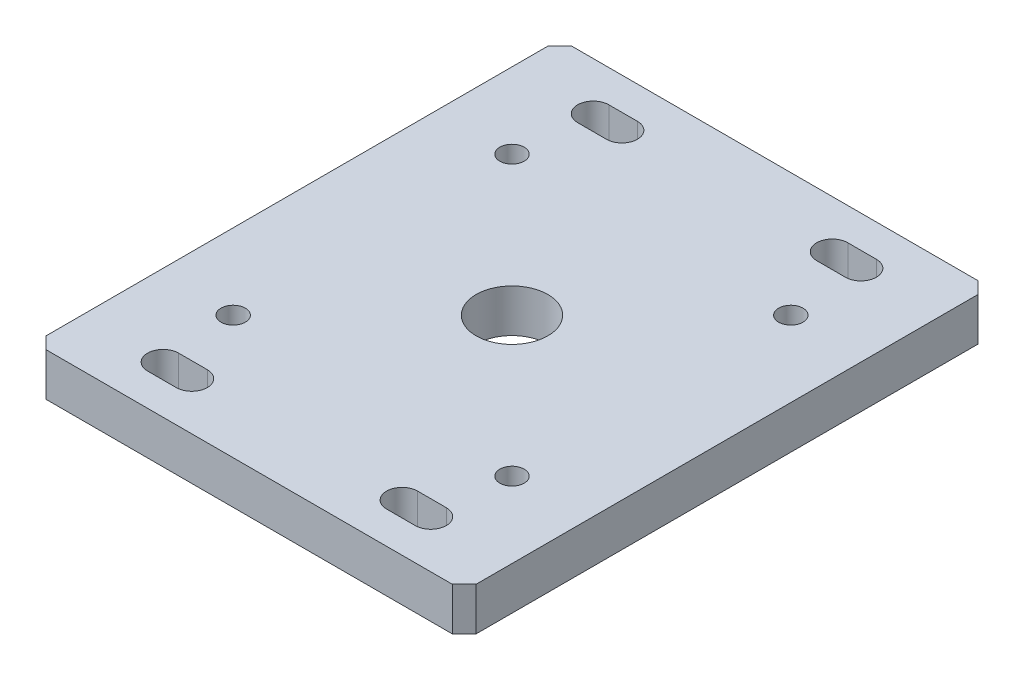
SolidWorks part; units mm, degrees
ref_plane "前基準面" through (0, 0, 0) normal (0, 0, 1) x (1, 0, 0)
ref_plane "上基準面" through (0, 0, 0) normal (0, 1, 0) x (1, 0, 0)
ref_plane "右基準面" through (0, 0, 0) normal (1, 0, 0) x (0, 0, -1)
sketch "草圖1" plane through (0, 0, 0) normal (1, 0, 0) x (0, 0, -1)
  line L1 (-110, 18) -> (110, 18)
  line L2 (-110, 18) -> (-110, 0)
  line L4 (110, 18) -> (110, 0)
  line L5 (-110, 0) -> (110, 0)
  line L7 (0, 36.9841) -> (0, -23.6317) construction
  dimension "D2" = 220
  dimension "D6" = 18
extrude "伸長1" add sketch "草圖1" along normal mid plane 180
sketch "草圖2" plane through (0, 0, 0) normal (0, -1, 0) x (1, 0, 0)
  circle A0 centre (0, 0) radius 15
  dimension "D1" = 30
extrude "除料-伸長1" cut sketch "草圖2" against normal up to next
chamfer "導角1" distance 5 angle 45 4 edges at (-90, 9, -110) (-90, 9, 110) (90, 9, 110) (90, 9, -110)
sketch "草圖4" plane through (0, 0, 0) normal (0, -1, 0) x (1, 0, 0)
  line L0 (-56, 90) -> (-44, 90) construction
  line L1 (44, 90) -> (56, 90) construction
  line L2 (-56, -90) -> (-44, -90) construction
  line L3 (44, -90) -> (56, -90) construction
  line L4 (-90, 105) -> (-90, -105) construction
  line L5 (-26.727, 0) -> (41, 0) construction
  line L6 (44, 83.5) -> (56, 83.5)
  line L7 (-56, 83.5) -> (-44, 83.5)
  line L8 (-56, -96.5) -> (-44, -96.5)
  line L9 (44, -96.5) -> (56, -96.5)
  line L10 (44, 96.5) -> (56, 96.5)
  line L11 (-56, 96.5) -> (-44, 96.5)
  line L12 (-56, -83.5) -> (-44, -83.5)
  line L13 (44, -83.5) -> (56, -83.5)
  line L14 (90, 105) -> (90, -105) construction
  arc A0 (44, 83.5) -> (44, 96.5) centre (44, 90) cw
  arc A1 (56, 83.5) -> (56, 96.5) centre (56, 90) ccw
  arc A2 (-56, 83.5) -> (-56, 96.5) centre (-56, 90) cw
  arc A3 (-44, 83.5) -> (-44, 96.5) centre (-44, 90) ccw
  arc A4 (-56, -96.5) -> (-56, -83.5) centre (-56, -90) cw
  arc A5 (-44, -96.5) -> (-44, -83.5) centre (-44, -90) ccw
  arc A6 (44, -96.5) -> (44, -83.5) centre (44, -90) cw
  arc A7 (56, -96.5) -> (56, -83.5) centre (56, -90) ccw
  point P8 (50, -90)
  point P30 (-50, -90)
  dimension "D1" = 12
  dimension "D2" = 40
  dimension "D3" = 40
  dimension "D4" = 180
  dimension "D5" = 6.5
  dimension "D6" = 6.5
extrude "除料-伸長3" cut sketch "草圖4" against normal up to next
hole_wizard "M12 螺紋孔1" positions "草圖11" profile "草圖10" tap size "M12" standard "GB" end condition up to next
sketch "草圖11" plane through (0, 18, 0) normal (0, 1, 0) x (-1, 0, 0)
  line L0 (0, 33.9575) -> (0, 0) construction
  line L1 (0, 0) -> (42.9727, 0) construction
  line L2 (58.3363, -58.3363) -> (-58.3363, -58.3363) construction
  line L3 (-58.3363, -58.3363) -> (-58.3363, 58.3363) construction
  circle A0 centre (0, 0) radius 82.5 construction
  point P0 (58.3363, 58.3363)
  point P1 (58.3363, -58.3363)
  point P3 (-58.3363, -58.3363)
  point P5 (-58.3363, 58.3363)
  dimension "D3" = 165
sketch "草圖10" plane through (-58.3363, 18, 58.3363) normal (1, 0, 0) x (0, 0, 1)
  line L0 (0, 0) -> (0, 18)
  line L1 (0, 18) -> (5.1, 18)
  line L2 (5.1, 18) -> (5.1, 0)
  line L5 (5.1, 0) -> (0, 0)
  line L11 (0, -6.35) -> (0, 107.95) construction
  dimension "貫穿螺孔鑽直徑" = 10.2
  dimension "貫穿螺孔鑽深度" = 18
cosmetic thread "鑽孔螺紋5" parameters "D2"=12
cosmetic thread "鑽孔螺紋6" parameters "D2"=12
cosmetic thread "鑽孔螺紋7" parameters "D2"=12
cosmetic thread "鑽孔螺紋8" parameters "D2"=12
